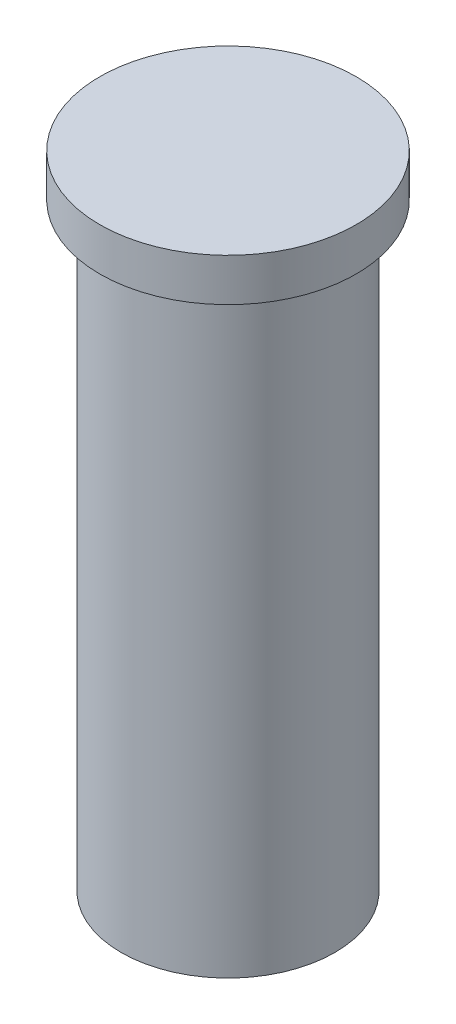
SolidWorks part; units mm, degrees
ref_plane "前视基准面" through (0, 0, 0) normal (0, 0, 1) x (1, 0, 0)
ref_plane "上视基准面" through (0, 0, 0) normal (0, 1, 0) x (1, 0, 0)
ref_plane "右视基准面" through (0, 0, 0) normal (1, 0, 0) x (0, 0, -1)
other "Configuration Table"
sketch "草图1" plane through (0, 0, 0) normal (0, 1, 0) x (1, 0, 0)
  circle A0 centre (0, 0) radius 25
  dimension "D1" = 50
extrude "凸台-拉伸1" add sketch "草图1" along normal blind 150 contours A0
sketch "草图2" plane through (0, 150, 0) normal (0, 1, 0) x (1, 0, 0)
  circle A0 centre (0, 0) radius 30
  dimension "D1" = 60
extrude "凸台-拉伸2" add sketch "草图2" against normal blind 10
